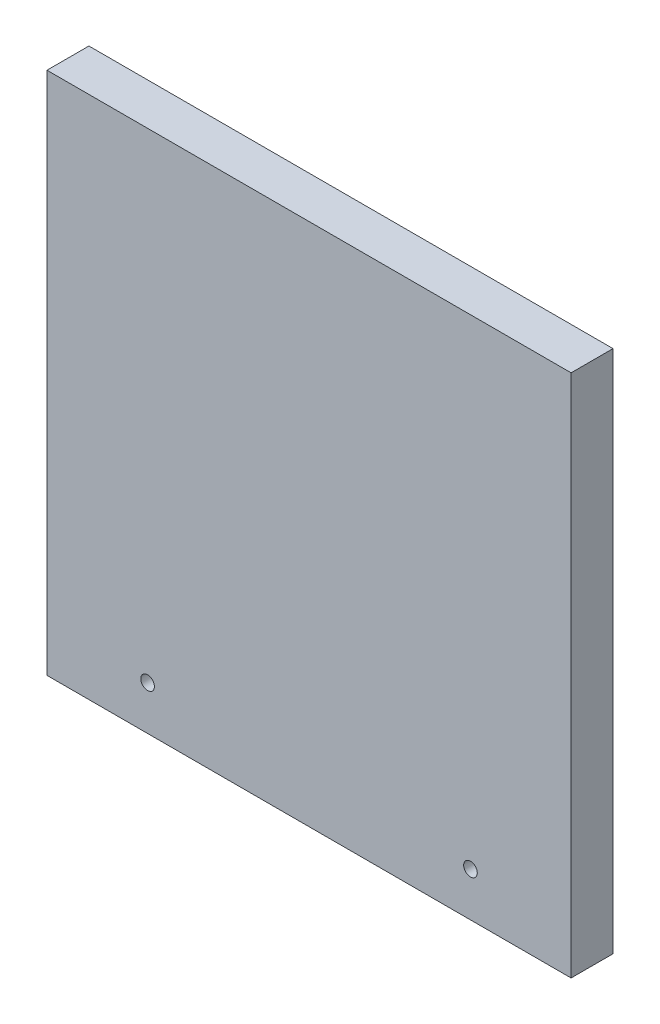
SolidWorks part; units mm, degrees
ref_plane "Alzado" through (0, 0, 0) normal (0, 0, 1) x (1, 0, 0)
ref_plane "Planta" through (0, 0, 0) normal (0, 1, 0) x (1, 0, 0)
ref_plane "Vista lateral" through (0, 0, 0) normal (1, 0, 0) x (0, 0, -1)
sketch "Croquis1" plane through (0, 0, 0) normal (0, 1, 0) x (1, 0, 0)
  line L1 (-130, 205.6) -> (130, 205.6) construction
  line L2 (-130, 205.6) -> (-130, -205.6) construction
  line L3 (-130, -205.6) -> (130, -205.6) construction
  line L4 (130, 205.6) -> (130, -205.6) construction
  line L5 (-130, 205.6) -> (130, -205.6) construction
  line L6 (-130, -205.6) -> (130, 205.6) construction
  line L7 (-125, 195.6) -> (125, 195.6)
  line L8 (-125, 195.6) -> (-125, 175.6)
  line L9 (-125, 175.6) -> (125, 175.6)
  line L10 (125, 195.6) -> (125, 175.6)
  line L11 (-125, 195.6) -> (125, 175.6) construction
  line L12 (-125, 175.6) -> (125, 195.6) construction
  point P0 (0, 0)
  point P6 (0, 185.6)
  point P11 (0, 0)
  dimension "D1" = 260
  dimension "D2" = 411.2
  dimension "D3" = 10
  dimension "D4" = 5
  dimension "D5" = 20
extrude "Saliente-Extruir1" add sketch "Croquis1" along normal blind 250
sketch "Croquis2" plane through (0, 0, -175.6) normal (0, 0, 1) x (1, 0, 0)
  line L0 (-125, 0) -> (125, 0) construction
  line L1 (-125, 250) -> (-125, 0) construction
  line L2 (0, 0) -> (0, 75.1261) construction
  circle A0 centre (-77, 21) radius 3.25
  circle A1 centre (77, 21) radius 3.25
  dimension "D1" = 6.5
  dimension "D2" = 21
  dimension "D3" = 48
extrude "Cortar-Extruir1" cut sketch "Croquis2" against normal through all
equation "\"baseWidth\"= 260"
equation "\"baseHeight\"= 411.20"
equation "\"marginSides\"= 5"
equation "\"marginTop\"= 10"
equation "\"D1@Croquis1\"=\"baseWidth\""
equation "\"D2@Croquis1\"=\"baseHeight\""
equation "\"D3@Croquis1\"=\"marginTop\""
equation "\"D4@Croquis1\"=\"marginSides\""
